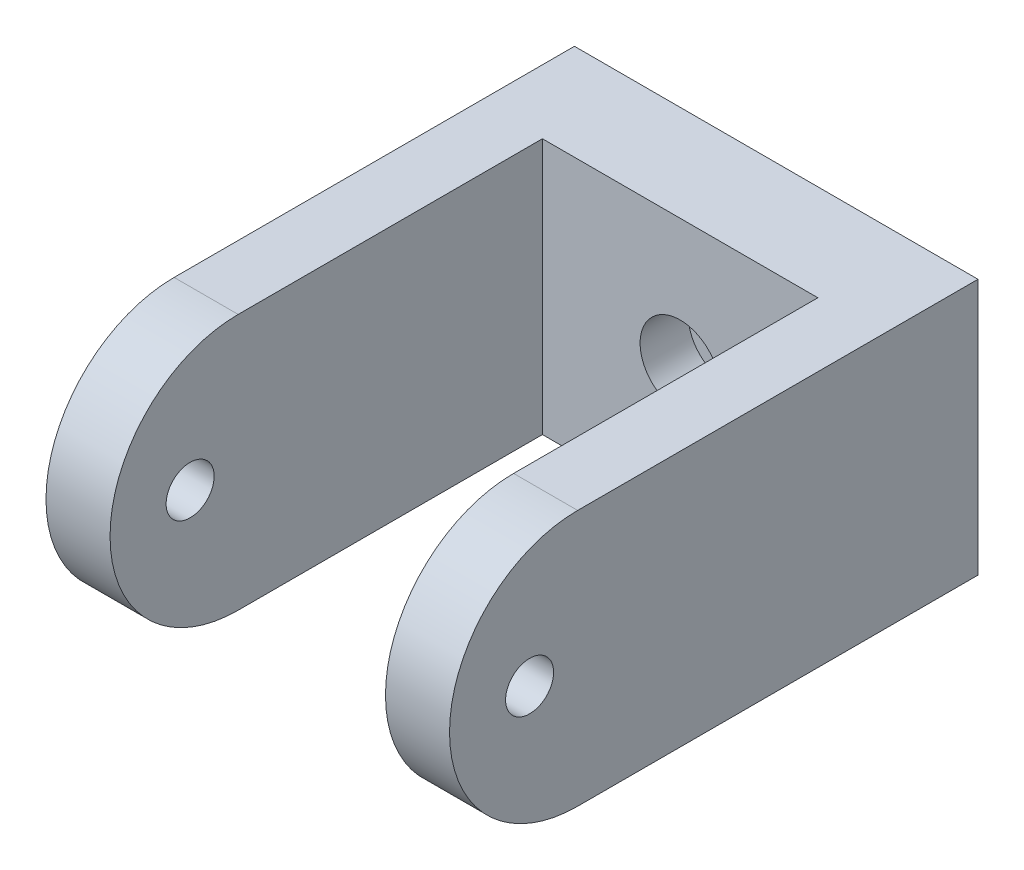
SolidWorks part; units mm, degrees
ref_plane "Ön Düzlem" through (0, 0, 0) normal (0, 0, 1) x (1, 0, 0)
ref_plane "Üst Düzlem" through (0, 0, 0) normal (0, 1, 0) x (1, 0, 0)
ref_plane "Sağ Düzlem" through (0, 0, 0) normal (1, 0, 0) x (0, 0, -1)
sketch "Çizim1" plane through (0, 0, 0) normal (0, 0, 1) x (1, 0, 0)
  line L1 (-3.8033, 1.4888) -> (21.3967, 1.4888)
  line L2 (-3.8033, 1.4888) -> (-3.8033, -14.5112)
  line L3 (-3.8033, -14.5112) -> (21.3967, -14.5112)
  line L4 (21.3967, 1.4888) -> (21.3967, -14.5112)
  dimension "D1" = 25.2
  dimension "D2" = 16
extrude "Yükseklik-Ekstrüzyon1" add sketch "Çizim1" along normal mid plane 6
ref_plane "Düzlem3" through (0, 0, 0) normal (0, 0, 1) x (1, 0, 0)
sketch "Çizim3" plane through (0, 0, 0) normal (0, 0, 1) x (1, 0, 0)
  line L0 (-3.8033, -14.5112) -> (21.3967, -14.5112) construction
  line L1 (-3.8033, 1.4888) -> (0.1967, 1.4888)
  line L2 (-3.8033, 1.4888) -> (-3.8033, -14.5112)
  line L3 (-3.8033, -14.5112) -> (0.1967, -14.5112)
  line L4 (0.1967, 1.4888) -> (0.1967, -14.5112)
  line L6 (21.3967, 1.4888) -> (17.3967, 1.4888)
  line L7 (21.3967, 1.4888) -> (21.3967, -14.5112)
  line L8 (21.3967, -14.5112) -> (17.3967, -14.5112)
  line L9 (17.3967, 1.4888) -> (17.3967, -14.5112)
  dimension "D1" = 16
  dimension "D2" = 4
  dimension "D3" = 4
extrude "Yükseklik-Ekstrüzyon2" add sketch "Çizim3" along normal blind 30
ref_plane "Düzlem4" through (0, 0, 0) normal (1, 0, 0) x (0, 0, -1)
sketch "Çizim4" plane through (0, 0, 0) normal (1, 0, 0) x (0, 0, -1)
  line L0 (-30, -14.5112) -> (-30, 1.4888) construction
  line L1 (-30, -6.5112) -> (-22, -6.5112) construction
  line L3 (-22, 1.4888) -> (-31.4686, 1.4888)
  line L4 (-31.4686, 1.4888) -> (-31.4686, -14.5112)
  line L6 (-22, -14.5112) -> (-31.4686, -14.5112)
  arc A1 (-22, 1.4888) -> (-22, -14.5112) centre (-22, -6.5112) ccw
  point P4 (-30, -6.5112)
  dimension "D1" = 8
extrude "Kes-Ekstrüzyon3" cut sketch "Çizim4" against normal mid plane 60
sketch "Çizim5" plane through (0, 0, 0) normal (1, 0, 0) x (0, 0, -1)
  line L0 (-30, -6.5112) -> (-25, -6.5112) construction
  arc A0 (-22, 1.4888) -> (-22, -14.5112) centre (-22, -6.5112) ccw construction
  circle A1 centre (-25, -6.5112) radius 1.5
  dimension "D2" = 3
  dimension "D1" = 5
extrude "Kes-Ekstrüzyon4" cut sketch "Çizim5" against normal mid plane 60
sketch "Çizim6" plane through (0, 0, 0) normal (0, 0, 1) x (1, 0, 0)
  line L0 (21.3967, -6.5112) -> (-4.3185, -6.5112) construction
  line L1 (21.3967, -14.5112) -> (21.3967, 1.4888) construction
  line L2 (8.7967, 1.4888) -> (8.7967, -15.876) construction
  line L3 (21.3967, 1.4888) -> (-3.8033, 1.4888) construction
  circle A0 centre (8.7967, -6.5112) radius 2.5
  dimension "D1" = 5
extrude "Kes-Ekstrüzyon5" cut sketch "Çizim6" along normal blind 4
sketch "Çizim7" plane through (0, 0, 0) normal (0, 0, 1) x (1, 0, 0)
  circle A0 centre (8.7967, -6.5112) radius 1
  dimension "D1" = 2
extrude "Kes-Ekstrüzyon6" cut sketch "Çizim7" against normal blind 15
